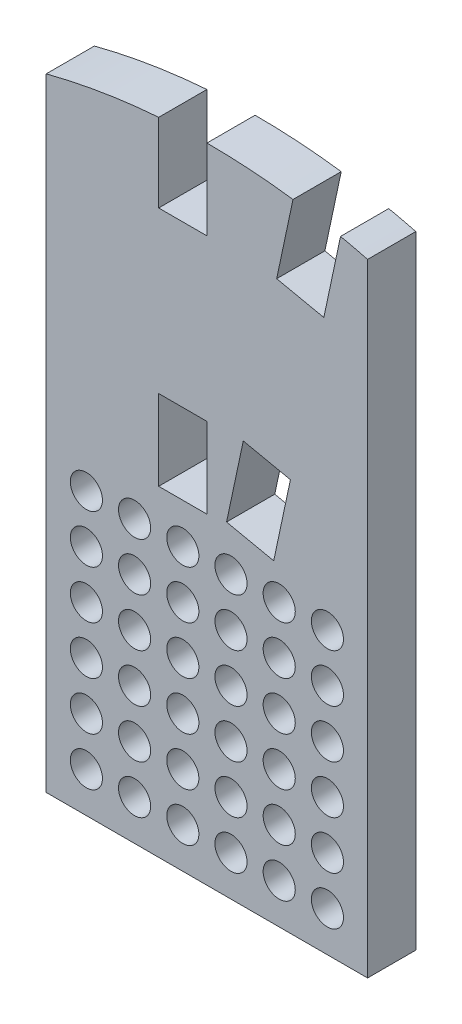
SolidWorks part; units mm, degrees
ref_plane "Front Plane" through (0, 0, 0) normal (0, 0, 1) x (1, 0, 0)
ref_plane "Top Plane" through (0, 0, 0) normal (0, 1, 0) x (1, 0, 0)
ref_plane "Right Plane" through (0, 0, 0) normal (1, 0, 0) x (0, 0, -1)
sketch "Sketch1" plane through (0, 0, 0) normal (0, 0, 1) x (1, 0, 0)
  line L0 (18.3165, 39.1259) -> (17.2769, 34.2352)
  line L1 (0, 0) -> (20, 0)
  line L2 (0, 0) -> (0, 38.7298)
  line L4 (20, 0) -> (20, 38.7298)
  line L6 (10, 40) -> (10, 35)
  line L7 (10, 35) -> (7, 35)
  line L8 (7, 39.8873) -> (7, 35)
  line L9 (7, 25) -> (10, 25)
  line L10 (7, 25) -> (7, 20)
  line L11 (18.3165, 39.1259) -> (17.2769, 34.2352)
  line L12 (15.3586, 39.6394) -> (14.3425, 34.8589)
  line L13 (17.2769, 34.2352) -> (14.3425, 34.8589)
  line L14 (7, 20) -> (10, 20)
  line L15 (10, 25) -> (10, 20)
  line L16 (14.1582, 19.563) -> (11.2238, 20.1867)
  line L17 (11.2238, 20.1867) -> (12.2633, 25.0774)
  line L18 (12.2633, 25.0774) -> (15.1978, 24.4537)
  line L19 (15.1978, 24.4537) -> (14.1582, 19.563)
  line L20 (13.6585, 34.8083) -> (10.6749, 35.1219) [skipped]
  line L21 (11.1858, 39.9824) -> (10.6749, 35.1219) [skipped]
  line L22 (14.1811, 39.7809) -> (13.6585, 34.8083) [skipped]
  circle A0 centre (2.5, 2.5) radius 1
  circle A1 centre (5.5, 2.5) radius 1
  circle A2 centre (8.5, 2.5) radius 1
  circle A3 centre (11.5, 2.5) radius 1
  circle A4 centre (14.5, 2.5) radius 1
  circle A5 centre (17.5, 2.5) radius 1
  circle A6 centre (5.5, 2.5) radius 1
  circle A7 centre (8.5, 2.5) radius 1
  circle A8 centre (11.5, 2.5) radius 1
  circle A9 centre (14.5, 2.5) radius 1
  circle A10 centre (17.5, 2.5) radius 1
  circle A11 centre (5.5, 5.5) radius 1
  circle A12 centre (8.5, 5.5) radius 1
  circle A13 centre (11.5, 5.5) radius 1
  circle A14 centre (14.5, 5.5) radius 1
  circle A15 centre (17.5, 5.5) radius 1
  circle A16 centre (5.5, 8.5) radius 1
  circle A17 centre (8.5, 8.5) radius 1
  circle A18 centre (11.5, 8.5) radius 1
  circle A19 centre (14.5, 8.5) radius 1
  circle A20 centre (17.5, 8.5) radius 1
  circle A21 centre (5.5, 11.5) radius 1
  circle A22 centre (8.5, 11.5) radius 1
  circle A23 centre (11.5, 11.5) radius 1
  circle A24 centre (14.5, 11.5) radius 1
  circle A25 centre (17.5, 11.5) radius 1
  circle A26 centre (5.5, 14.5) radius 1
  circle A27 centre (8.5, 14.5) radius 1
  circle A28 centre (11.5, 14.5) radius 1
  circle A29 centre (14.5, 14.5) radius 1
  circle A30 centre (17.5, 14.5) radius 1
  circle A31 centre (5.5, 17.5) radius 1
  circle A32 centre (8.5, 17.5) radius 1
  circle A33 centre (11.5, 17.5) radius 1
  circle A34 centre (14.5, 17.5) radius 1
  circle A35 centre (17.5, 17.5) radius 1
  circle A36 centre (2.5, 5.5) radius 1
  circle A37 centre (2.5, 8.5) radius 1
  circle A38 centre (2.5, 11.5) radius 1
  circle A39 centre (2.5, 14.5) radius 1
  circle A40 centre (2.5, 17.5) radius 1
  arc A41 (10, 40) -> (20, 38.7298) centre (10, 0) cw
  arc A42 (10, 40) -> (0, 38.7298) centre (10, 0) ccw
  point P102 (10, 0)
  point P108 (10, 0)
  dimension "D3" = 2
  dimension "D1" = 20
  dimension "D2" = 40
  dimension "D4" = 2.5
  dimension "D5" = 2.5
  dimension "D9" = 3
  dimension "D10" = 5
  dimension "D11" = 5
  dimension "D12" = 3
  dimension "D14" = 10
  dimension "D15" = 20
  dimension "D16" = 3
  dimension "D17" = 5
  dimension "D6" = 6
  dimension "D7" = 6
  dimension "D8" = 6
  dimension "D13" = 3
extrude "Boss-Extrude1" add sketch "Sketch1" along normal blind 3
